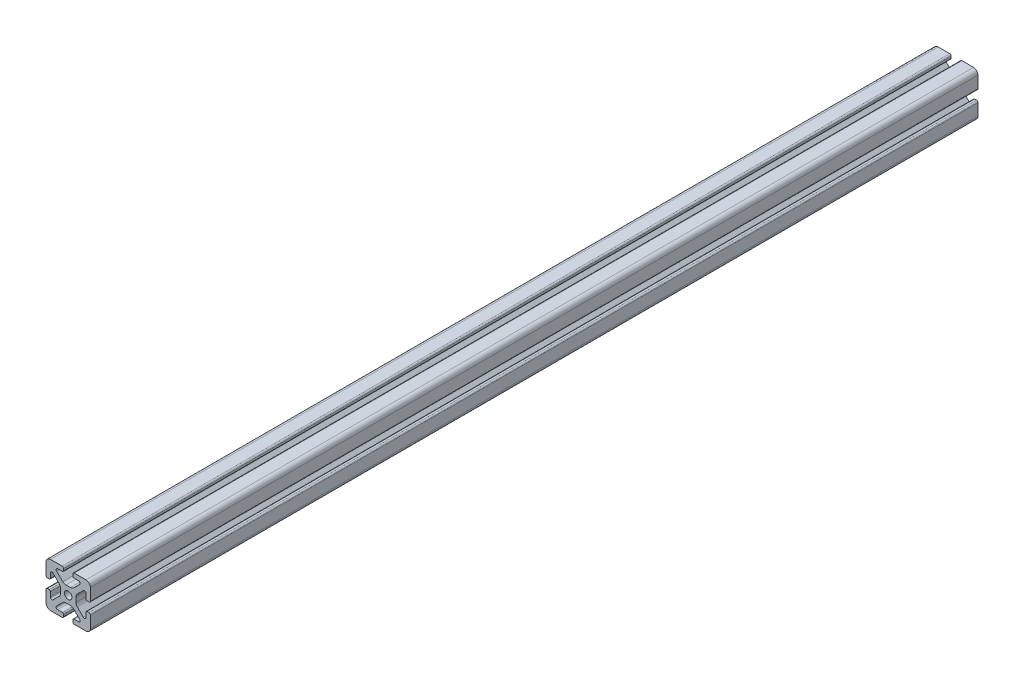
SolidWorks part; units mm, degrees
material "Alliage 1060"
ref_plane "Plan de face" through (0, 0, 0) normal (0, 0, 1) x (1, 0, 0)
ref_plane "Plan de dessus" through (0, 0, 0) normal (0, 1, 0) x (1, 0, 0)
ref_plane "Plan de droite" through (0, 0, 0) normal (1, 0, 0) x (0, 0, -1)
sketch "Esquisse1" plane through (0, 0, 0) normal (0, 0, 1) x (1, 0, 0)
  line L108 (-5.25, 1.6032) -> (-5.25, -1.6032)
  line L109 (-6.1287, -3.7245) -> (-10.2547, -7.8506)
  line L110 (-12, -7.1276) -> (-12, -3.9)
  line L111 (-12.8, -3.1) -> (-14, -3.1)
  line L112 (-15, -4.1) -> (-15, -12)
  line L113 (-12, -15) -> (-4.1, -15)
  line L114 (-3.1, -14) -> (-3.1, -12.8)
  line L115 (-3.9, -12) -> (-7.1276, -12)
  line L116 (-7.8506, -10.2547) -> (-3.7245, -6.1287)
  line L117 (-1.6032, -5.25) -> (1.6032, -5.25)
  line L118 (3.7245, -6.1287) -> (7.8506, -10.2547)
  line L119 (7.1276, -12) -> (3.9, -12)
  line L120 (3.1, -12.8) -> (3.1, -14)
  line L121 (4.1, -15) -> (12, -15)
  line L122 (15, -12) -> (15, -4.1)
  line L123 (14, -3.1) -> (12.8, -3.1)
  line L124 (12, -3.9) -> (12, -7.1276)
  line L125 (10.2547, -7.8506) -> (6.1287, -3.7245)
  line L126 (5.25, -1.6032) -> (5.25, 1.6032)
  line L127 (6.1287, 3.7245) -> (10.2547, 7.8506)
  line L128 (12, 7.1276) -> (12, 3.9)
  line L129 (12.8, 3.1) -> (14, 3.1)
  line L130 (15, 4.1) -> (15, 12)
  line L131 (12, 15) -> (4.1, 15)
  line L132 (3.1, 14) -> (3.1, 12.8)
  line L133 (3.9, 12) -> (7.1276, 12)
  line L134 (7.8506, 10.2547) -> (3.7245, 6.1287)
  line L135 (1.6032, 5.25) -> (-1.6032, 5.25)
  line L136 (-3.7245, 6.1287) -> (-7.8506, 10.2547)
  line L137 (-7.1276, 12) -> (-3.9, 12)
  line L138 (-3.1, 12.8) -> (-3.1, 14)
  line L139 (-4.1, 15) -> (-12, 15)
  line L140 (-15, 12) -> (-15, 4.1)
  line L141 (-14, 3.1) -> (-12.8, 3.1)
  line L142 (-12, 3.9) -> (-12, 7.1276)
  line L143 (-10.2547, 7.8506) -> (-6.1287, 3.7245)
  arc A42 (-2.5, 0) -> (2.5, 0) centre (0, 0) ccw
  arc A43 (2.5, 0) -> (-2.5, 0) centre (0, 0) ccw
  arc A108 (-5.25, 1.6032) -> (-6.1287, 3.7245) centre (-8.25, 1.6032) ccw
  arc A109 (-6.1287, -3.7245) -> (-5.25, -1.6032) centre (-8.25, -1.6032) ccw
  arc A110 (-12, -7.1276) -> (-10.2547, -7.8506) centre (-10.9776, -7.1276) ccw
  arc A111 (-12, -3.9) -> (-12.8, -3.1) centre (-12.8, -3.9) ccw
  arc A112 (-14, -3.1) -> (-15, -4.1) centre (-14, -4.1) ccw
  arc A113 (-15, -12) -> (-12, -15) centre (-12, -12) ccw
  arc A114 (-4.1, -15) -> (-3.1, -14) centre (-4.1, -14) ccw
  arc A115 (-3.1, -12.8) -> (-3.9, -12) centre (-3.9, -12.8) ccw
  arc A116 (-7.8506, -10.2547) -> (-7.1276, -12) centre (-7.1276, -10.9776) ccw
  arc A117 (-1.6032, -5.25) -> (-3.7245, -6.1287) centre (-1.6032, -8.25) ccw
  arc A118 (3.7245, -6.1287) -> (1.6032, -5.25) centre (1.6032, -8.25) ccw
  arc A119 (7.1276, -12) -> (7.8506, -10.2547) centre (7.1276, -10.9776) ccw
  arc A120 (3.9, -12) -> (3.1, -12.8) centre (3.9, -12.8) ccw
  arc A121 (3.1, -14) -> (4.1, -15) centre (4.1, -14) ccw
  arc A122 (12, -15) -> (15, -12) centre (12, -12) ccw
  arc A123 (15, -4.1) -> (14, -3.1) centre (14, -4.1) ccw
  arc A124 (12.8, -3.1) -> (12, -3.9) centre (12.8, -3.9) ccw
  arc A125 (10.2547, -7.8506) -> (12, -7.1276) centre (10.9776, -7.1276) ccw
  arc A126 (5.25, -1.6032) -> (6.1287, -3.7245) centre (8.25, -1.6032) ccw
  arc A127 (6.1287, 3.7245) -> (5.25, 1.6032) centre (8.25, 1.6032) ccw
  arc A128 (12, 7.1276) -> (10.2547, 7.8506) centre (10.9776, 7.1276) ccw
  arc A129 (12, 3.9) -> (12.8, 3.1) centre (12.8, 3.9) ccw
  arc A130 (14, 3.1) -> (15, 4.1) centre (14, 4.1) ccw
  arc A131 (15, 12) -> (12, 15) centre (12, 12) ccw
  arc A132 (4.1, 15) -> (3.1, 14) centre (4.1, 14) ccw
  arc A133 (3.1, 12.8) -> (3.9, 12) centre (3.9, 12.8) ccw
  arc A134 (7.8506, 10.2547) -> (7.1276, 12) centre (7.1276, 10.9776) ccw
  arc A135 (1.6032, 5.25) -> (3.7245, 6.1287) centre (1.6032, 8.25) ccw
  arc A136 (-3.7245, 6.1287) -> (-1.6032, 5.25) centre (-1.6032, 8.25) ccw
  arc A137 (-7.1276, 12) -> (-7.8506, 10.2547) centre (-7.1276, 10.9776) ccw
  arc A138 (-3.9, 12) -> (-3.1, 12.8) centre (-3.9, 12.8) ccw
  arc A139 (-3.1, 14) -> (-4.1, 15) centre (-4.1, 14) ccw
  arc A140 (-12, 15) -> (-15, 12) centre (-12, 12) ccw
  arc A141 (-15, 4.1) -> (-14, 3.1) centre (-14, 4.1) ccw
  arc A142 (-12.8, 3.1) -> (-12, 3.9) centre (-12.8, 3.9) ccw
  arc A143 (-10.2547, 7.8506) -> (-12, 7.1276) centre (-10.9776, 7.1276) ccw
extrude "Boss.-Extru.1" add sketch "Esquisse1" along normal blind 600
